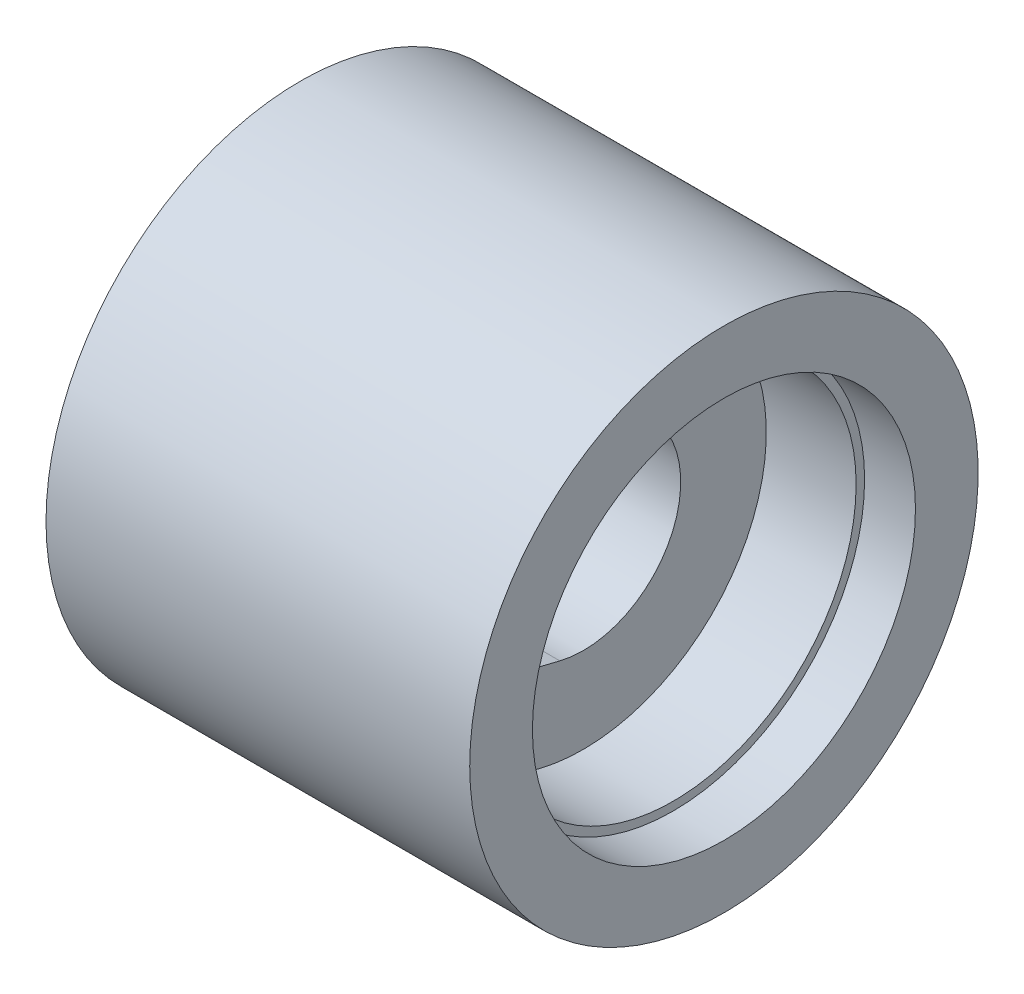
SolidWorks part; units mm, degrees
ref_plane "前视基准面" through (0, 0, 0) normal (0, 0, 1) x (1, 0, 0)
ref_plane "上视基准面" through (0, 0, 0) normal (0, 1, 0) x (1, 0, 0)
ref_plane "右视基准面" through (0, 0, 0) normal (1, 0, 0) x (0, 0, -1)
sketch "Sketch1" plane through (0, 0, 0) normal (0, 0, 1) x (1, 0, 0)
  line L0 (0, 0) -> (251.577, 0) construction
  line L1 (0, 0) -> (0, 113) construction
  line L2 (0, 113) -> (-30, 113)
  line L3 (-30, 113) -> (-30, 108)
  line L4 (-30, 108) -> (-83, 108)
  line L5 (-83, 108) -> (-83, 57.5)
  line L6 (-83, 57.5) -> (-250, 57.5)
  line L7 (-250, 57.5) -> (-250, 0) construction
  line L8 (-250, 0) -> (0, 0) construction
  line L9 (0, 113) -> (0, 150)
  line L10 (0, 150) -> (-250, 150)
  line L11 (-250, 150) -> (-250, 57.5)
  dimension "D1" = 226
  dimension "D2" = 216
  dimension "D3" = 115
  dimension "D4" = 30
  dimension "D5" = 83
  dimension "D6" = 250
  dimension "D7" = 300
revolve "Revolve1" add sketch "Sketch1" angle 360 about L0
sketch "Sketch2" plane through (-250, 0, 0) normal (-1, 0, 0) x (0, 0, 1)
  line L0 (13.8, -55.8194) -> (108.04, -32.5209)
  line L1 (13.8, 55.8194) -> (108.04, 32.5209)
  line L2 (0, 0) -> (100, 0) construction
  arc A0 (108.04, -32.5209) -> (108.04, 32.5209) centre (100, 0) ccw
  circle A1 centre (0, 0) radius 57.5 construction
  arc A2 (13.8, 55.8194) -> (13.8, -55.8194) centre (0, 0) cw
  dimension "D1" = 67
  dimension "D3" = 57.5
  dimension "D2" = 100
extrude "Extrude1" cut sketch "Sketch2" against normal up to surface (167 mm away) up to face at (-83, 0, 108)
sketch "Sketch5" plane through (0, 0, 0) normal (0, 0, 1) x (1, 0, 0)
  line L0 (0, 100) -> (157.9794, 100) construction
  line L1 (0, -150) -> (0, 150) construction
  line L2 (0, 0) -> (-250, 0) construction
  line L4 (0, 0) -> (0, 177.7863) construction
  line L5 (-125, 135.5) -> (-262.5372, 135.5)
  line L6 (-262.5372, 135.5) -> (-262.5372, 100)
  line L7 (-262.5372, 100) -> (-106, 100)
  line L9 (-125, 127.5) -> (-122, 127.5)
  line L10 (-122, 127.5) -> (-122, 128.5)
  line L11 (-122, 128.5) -> (-121, 128.5)
  line L12 (-121, 128.5) -> (-121, 127.5)
  line L13 (-121, 127.5) -> (-108, 127.5)
  line L14 (-108, 127.5) -> (-108, 125)
  line L15 (-108, 125) -> (-106, 125)
  line L16 (-106, 125) -> (-106, 100)
  line L17 (-125, 135.5) -> (-125, 127.5)
  dimension "D1" = 100
  dimension "D2" = 125
  dimension "D3" = 3
  dimension "D4" = 1
  dimension "D5" = 71
  dimension "D6" = 55
  dimension "D7" = 13
  dimension "D8" = 50
  dimension "D9" = 2
revolve "Cut-Revolve1" cut sketch "Sketch5" angle 360 about L7
sketch "Sketch6" plane through (-250, 0, 0) normal (-1, 0, 0) x (0, 0, 1)
  line L0 (-34.6302, 107.81) -> (-56.0912, 12.65)
  line L1 (0, 100) -> (0, 0) construction
  line L2 (34.6302, 107.81) -> (56.0912, 12.65)
  arc A0 (-56.0912, 12.65) -> (56.0912, 12.65) centre (0, 0) ccw
  arc A1 (34.6302, 107.81) -> (-34.6302, 107.81) centre (0, 100) ccw
  dimension "D1" = 115
  dimension "D2" = 71
extrude "Extrude2" cut sketch "Sketch6" against normal up to surface (125 mm away) up to face at (-125, 100, 35.5)
sketch "Sketch7" plane through (0, 0, 0) normal (0, 1, 0) x (1, 0, 0)
  line L0 (0, 0) -> (205.7427, 0) construction
  line L1 (0, 0) -> (0, 204.3465) construction
  line L2 (-250, 135.5) -> (-173, 135.5)
  line L3 (-173, 135.5) -> (-173, 127.5)
  line L4 (-173, 127.5) -> (-170, 127.5)
  line L5 (-170, 127.5) -> (-170, 128.5)
  line L6 (-170, 128.5) -> (-169, 128.5)
  line L7 (-169, 128.5) -> (-169, 127.5)
  line L8 (-169, 127.5) -> (-156, 127.5)
  line L9 (-156, 127.5) -> (-156, 125)
  line L10 (-156, 125) -> (-154, 125)
  line L11 (-154, 125) -> (-154, 100)
  line L14 (-154, 100) -> (-250, 100)
  line L15 (-250, 100) -> (-250, 135.5)
  line L16 (-154, 100) -> (11.2471, 100) construction
  line L17 (-250, 150) -> (-250, -150) construction
  dimension "D1" = 100
  dimension "D2" = 50
  dimension "D3" = 55
  dimension "D4" = 2
  dimension "D5" = 1
  dimension "D6" = 3
  dimension "D7" = 71
  dimension "D8" = 173
  dimension "D9" = 13
revolve "Cut-Revolve2" cut sketch "Sketch7" angle 360 about L14
sketch "Sketch8" plane through (-250, 0, 0) normal (-1, 0, 0) x (0, 0, 1)
  line L0 (-100, 0) -> (0, 0) construction
  line L1 (-107.81, 34.6302) -> (-12.65, 56.0912)
  line L2 (-107.81, -34.6302) -> (-12.65, -56.0912)
  circle A0 centre (-100, 0) radius 35.5 construction
  arc A1 (-107.81, 34.6302) -> (-107.81, -34.6302) centre (-100, 0) ccw
  arc A2 (-12.65, -56.0912) -> (-12.65, 56.0912) centre (0, 0) ccw
  dimension "D1" = 115
extrude "Extrude3" cut sketch "Sketch8" against normal up to surface (77 mm away) up to face at (-173, 0, -135.5)
ref_plane "Plane2" through (0, -150, 0) normal (0, -1, 0) x (-1, 0, 0)
sketch "Sketch10" plane through (0, -150, 0) normal (0, -1, 0) x (-1, 0, 0)
  line L0 (250, 0) -> (0, 0) construction
  line L1 (250, -150) -> (250, 150) construction
  circle A0 centre (125, 0) radius 15
  dimension "D1" = 30
extrude "Extrude4" cut sketch "Sketch10" against normal blind 1
